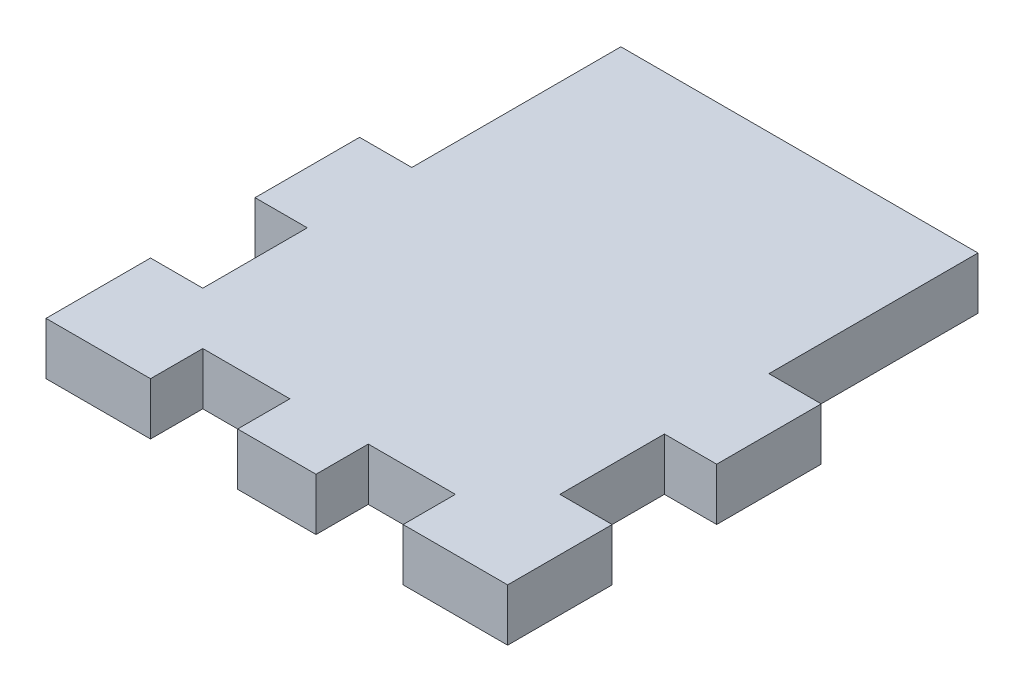
SolidWorks part; units mm, degrees
ref_plane "Plano frontal" through (0, 0, 0) normal (0, 0, 1) x (1, 0, 0)
ref_plane "Plano superior" through (0, 0, 0) normal (0, 1, 0) x (1, 0, 0)
ref_plane "Plano direito" through (0, 0, 0) normal (1, 0, 0) x (0, 0, -1)
sketch "ParedeLado2Esboco" plane through (0, 0, 0) normal (0, 1, 0) x (1, 0, 0)
  line L0 (0, 0) -> (0, 6)
  line L1 (0, 6) -> (3, 6)
  line L2 (3, 6) -> (3, 12)
  line L3 (3, 12) -> (0, 12)
  line L4 (0, 12) -> (0, 18)
  line L5 (0, 18) -> (3, 18)
  line L6 (3, 18) -> (3, 30)
  line L7 (3, 30) -> (23.5, 30)
  line L8 (23.5, 30) -> (23.5, 18)
  line L9 (23.5, 18) -> (26.5, 18)
  line L10 (26.5, 18) -> (26.5, 12)
  line L11 (26.5, 12) -> (23.5, 12)
  line L12 (23.5, 12) -> (23.5, 6)
  line L13 (23.5, 6) -> (26.5, 6)
  line L14 (26.5, 6) -> (26.5, 0)
  line L15 (26.5, 0) -> (20.5, 0)
  line L16 (20.5, 0) -> (20.5, 3)
  line L17 (20.5, 3) -> (15.5, 3)
  line L18 (15.5, 3) -> (15.5, 0)
  line L19 (15.5, 0) -> (11, 0)
  line L20 (11, 0) -> (11, 3)
  line L21 (11, 3) -> (6, 3)
  line L22 (6, 3) -> (6, 0)
  line L23 (6, 0) -> (0, 0)
  point P9 (0, 0)
  dimension "D1" = 26.5
  dimension "D2" = 3
  dimension "D3" = 3
  dimension "D4" = 3
  dimension "D5" = 30
  dimension "D6" = 6
  dimension "D7" = 6
  dimension "D8" = 6
  dimension "D9" = 6
  dimension "D10" = 6
  dimension "D11" = 5
  dimension "D12" = 5
extrude "ParedeLado2" add sketch "ParedeLado2Esboco" along normal blind 3
